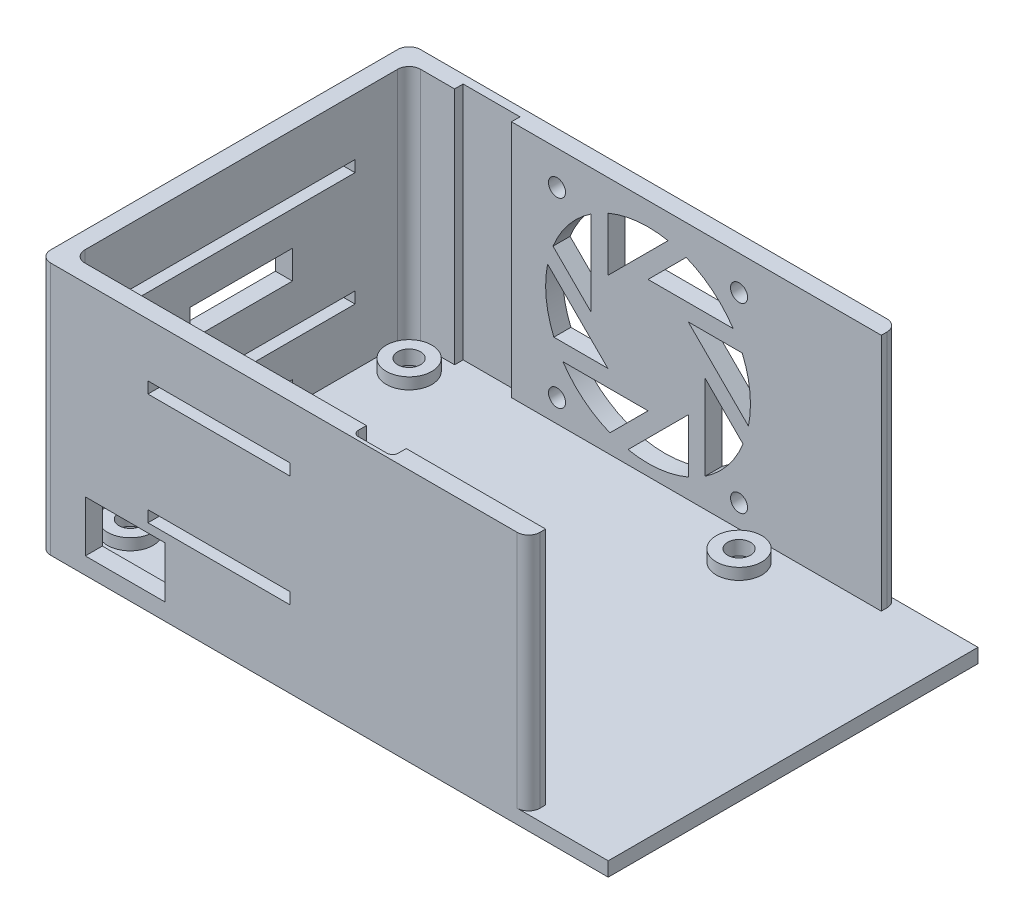
SolidWorks part; units mm, degrees
ref_plane "Front Plane" through (0, 0, 0) normal (0, 0, 1) x (1, 0, 0)
ref_plane "Top Plane" through (0, 0, 0) normal (0, 1, 0) x (1, 0, 0)
ref_plane "Right Plane" through (0, 0, 0) normal (1, 0, 0) x (0, 0, -1)
sketch "Sketch1" plane through (0, 0, 0) normal (0, 1, 0) x (1, 0, 0)
  line L1 (-50, 32.5) -> (50, 32.5)
  line L2 (-50, 32.5) -> (-50, -32.5)
  line L3 (-50, -32.5) -> (50, -32.5)
  line L4 (50, 32.5) -> (50, -32.5)
  line L5 (-50, 32.5) -> (50, -32.5) construction
  line L6 (-50, -32.5) -> (50, 32.5) construction
  point P0 (0, 0)
  dimension "D1" = 100
  dimension "D2" = 65
extrude "Boss-Extrude1" add sketch "Sketch1" along normal blind 2.5
sketch "Sketch2" plane through (0, 2.5, 0) normal (0, 1, 0) x (1, 0, 0)
  line L0 (-13, 32.5) -> (-13, -32.5) construction
  line L1 (50, 32.5) -> (-50, 32.5) construction
  line L2 (-50, -32.5) -> (50, -32.5) construction
  line L3 (-50, 0) -> (50, 0) construction
  line L4 (-50, 32.5) -> (-50, -32.5) construction
  line L5 (50, -32.5) -> (50, 32.5) construction
  line L6 (-42, -24.5) -> (-42, 24.5) construction
  line L7 (16, -24.5) -> (16, 24.5) construction
  circle A0 centre (-42, 24.5) radius 2
  circle A1 centre (-42, -24.5) radius 2
  circle A2 centre (16, -24.5) radius 2
  circle A3 centre (16, 24.5) radius 2
  point P17 (-42, 0)
  point P22 (16, 0)
  dimension "D1" = 4
  dimension "D2" = 24.5
  dimension "D3" = 29
  dimension "D4" = 13
extrude "Cut-Extrude1" cut sketch "Sketch2" against normal through all
sketch "Sketch3" plane through (0, 2.5, 0) normal (0, 1, 0) x (1, 0, 0)
  circle A0 centre (-42, 24.5) radius 4
  circle A1 centre (-42, 24.5) radius 2
  circle A2 centre (16, 24.5) radius 2
  circle A3 centre (16, 24.5) radius 4
  circle A4 centre (16, -24.5) radius 4
  circle A5 centre (16, -24.5) radius 2
  circle A6 centre (-42, -24.5) radius 2
  circle A7 centre (-42, -24.5) radius 4
  circle A8 centre (-42, 24.5) radius 2 construction
  circle A9 centre (-42, -24.5) radius 2 construction
  circle A10 centre (16, 24.5) radius 2 construction
  circle A11 centre (16, -24.5) radius 2 construction
  dimension "D3" = 2
extrude "Boss-Extrude2" add sketch "Sketch3" along normal blind 2
sketch "Sketch4" plane through (0, 0, 0) normal (0, -1, 0) x (-1, 0, 0)
  line L0 (50, 0) -> (-50, 0) construction
  line L1 (42, -28.1084) -> (45.125, -26.3042)
  line L2 (45.125, -26.3042) -> (45.125, -22.6958)
  line L3 (45.125, -22.6958) -> (42, -20.8916)
  line L4 (42, -20.8916) -> (38.875, -22.6958)
  line L5 (38.875, -22.6958) -> (38.875, -26.3042)
  line L6 (38.875, -26.3042) -> (42, -28.1084)
  line L7 (50, 32.5) -> (50, -32.5) construction
  line L8 (-50, -32.5) -> (-50, 32.5) construction
  line L9 (-16, -24.5) -> (42, -24.5) construction
  line L10 (13, -24.5) -> (13, 24.5) construction
  line L11 (-12.875, -26.3042) -> (-16, -28.1084)
  line L12 (-12.875, -22.6958) -> (-12.875, -26.3042)
  line L13 (-16, -20.8916) -> (-12.875, -22.6958)
  line L14 (-19.125, -22.6958) -> (-16, -20.8916)
  line L15 (-16, -28.1084) -> (-19.125, -26.3042)
  line L16 (-19.125, -26.3042) -> (-19.125, -22.6958)
  line L17 (-16, 24.5) -> (42, 24.5) construction
  line L18 (-19.125, 26.3042) -> (-19.125, 22.6958)
  line L19 (-16, 28.1084) -> (-19.125, 26.3042)
  line L20 (-19.125, 22.6958) -> (-16, 20.8916)
  line L21 (-16, 20.8916) -> (-12.875, 22.6958)
  line L22 (-12.875, 22.6958) -> (-12.875, 26.3042)
  line L23 (-12.875, 26.3042) -> (-16, 28.1084)
  line L24 (38.875, 26.3042) -> (42, 28.1084)
  line L25 (38.875, 22.6958) -> (38.875, 26.3042)
  line L26 (42, 20.8916) -> (38.875, 22.6958)
  line L27 (45.125, 22.6958) -> (42, 20.8916)
  line L28 (45.125, 26.3042) -> (45.125, 22.6958)
  line L29 (42, 28.1084) -> (45.125, 26.3042)
  circle A0 centre (42, -24.5) radius 3.125 construction
  circle A1 centre (-16, -24.5) radius 3.125 construction
  circle A2 centre (-16, 24.5) radius 3.125 construction
  circle A3 centre (42, 24.5) radius 3.125 construction
  point P31 (13, 0)
  dimension "D1" = 6.25
extrude "Cut-Extrude2" cut sketch "Sketch4" against normal blind 2
sketch "Sketch5" plane through (0, 2.5, 0) normal (0, 1, 0) x (1, 0, 0)
  line L0 (-50, 0) -> (50, 0) construction
  line L1 (-50, 32.5) -> (-50, -32.5) construction
  line L2 (50, -32.5) -> (50, 32.5) construction
  line L4 (-25, -9) -> (-50, -9)
  line L5 (-25, -9) -> (-25, 9)
  line L6 (-25, 9) -> (-50, 9)
  line L7 (-50, -9) -> (-50, 9)
  line L8 (-25, -9) -> (-50, 9) construction
  line L9 (-25, 9) -> (-50, -9) construction
  point P6 (-37.5, 0)
  dimension "D1" = 25
  dimension "D2" = 18
extrude "Cut-Extrude3" cut sketch "Sketch5" against normal blind 1
sketch "Sketch6" plane through (0, 2.5, 0) normal (0, 1, 0) x (1, 0, 0)
  line L0 (-50, 0) -> (0, 0) construction
  line L1 (-50, 32.5) -> (36, 32.5)
  line L2 (-50, 32.5) -> (-50, 29.5)
  line L3 (-50, 29.5) -> (36, 29.5)
  line L4 (36, 32.5) -> (36, 29.5)
  line L5 (-50, 9) -> (-50, -9) construction
  line L7 (36, -32.5) -> (36, -29.5)
  line L8 (-50, -29.5) -> (36, -29.5)
  line L9 (-50, -32.5) -> (-50, -29.5)
  line L10 (-50, -32.5) -> (36, -32.5)
  circle A0 centre (16, 24.5) radius 2 construction
  dimension "D1" = 3
  dimension "D2" = 20
extrude "Boss-Extrude3" add sketch "Sketch6" along normal blind 42
sketch "Sketch7" plane through (0, 44.5, 0) normal (0, 1, 0) x (1, 0, 0)
  line L0 (7.9988, -30.5371) -> (7.9988, -29.5) construction
  line L1 (6.0238, -30.5371) -> (9.9738, -30.5371) construction
  line L2 (36, -29.5) -> (-50, -29.5) construction
  line L3 (10.4988, -30.3621) -> (10.4988, -28.0371) construction
  line L4 (4.4988, -27.1) -> (11.4988, -27.1)
  line L5 (4.4988, -27.1) -> (4.4988, -30.9)
  line L6 (5.4988, -31.9) -> (10.4988, -31.9)
  line L7 (11.4988, -27.1) -> (11.4988, -30.9)
  line L8 (4.4988, -27.1) -> (11.4988, -31.9) construction
  line L9 (4.4988, -31.9) -> (11.4988, -27.1) construction
  line L10 (-50, -32.5) -> (36, -32.5) construction
  arc A0 (10.4988, -31.9) -> (11.4988, -30.9) centre (10.4988, -30.9) ccw
  arc A1 (4.4988, -30.9) -> (5.4988, -31.9) centre (5.4988, -30.9) ccw
  dimension "D3" = 1
  dimension "D1" = 1
  dimension "D2" = 0.6
extrude "Cut-Extrude4" cut sketch "Sketch7" against normal up to surface (42 mm away) up to face at (16, 2.5, 28.5)
sketch "Sketch8" plane through (0, 2.5, 0) normal (0, 1, 0) x (1, 0, 0)
  line L0 (-50, 29.5) -> (36, 29.5) construction
  line L1 (-50, 9) -> (-47, 9)
  line L2 (-50, 9) -> (-50, 29.5)
  line L3 (-50, 29.5) -> (-47, 29.5)
  line L4 (-47, 9) -> (-47, 29.5)
  line L5 (4.4988, -29.5) -> (-50, -29.5) construction
  line L6 (-50, -9) -> (-47, -9)
  line L7 (-50, -9) -> (-50, -29.5)
  line L8 (-50, -29.5) -> (-47, -29.5)
  line L9 (-47, -9) -> (-47, -29.5)
  line L10 (-50, 32.5) -> (-50, 29.5) construction
extrude "Boss-Extrude4" add sketch "Sketch8" along normal up to surface (42 mm away) up to face at (-7, 44.5, -31)
sketch "Sketch9" plane through (-50, 0, 0) normal (-1, 0, 0) x (0, 0, 1)
  line L0 (-9, 14) -> (9, 14) construction
  line L1 (-9, 1.5) -> (-9, 44.5) construction
  line L2 (9, 1.5) -> (9, 44.5) construction
  line L4 (-9, 6.5) -> (9, 6.5)
  line L5 (-9, 6.5) -> (-9, 21.5)
  line L6 (-9, 21.5) -> (9, 21.5)
  line L7 (9, 6.5) -> (9, 21.5)
  line L8 (-9, 6.5) -> (9, 21.5) construction
  line L9 (-9, 21.5) -> (9, 6.5) construction
  line L10 (-9, 1.5) -> (9, 1.5) construction
  line L11 (-9, 44.5) -> (9, 44.5)
  line L12 (-9, 44.5) -> (-9, 26.5)
  line L13 (-9, 26.5) -> (9, 26.5)
  line L14 (9, 44.5) -> (9, 26.5)
  point P6 (0, 14)
  dimension "D1" = 5
  dimension "D2" = 5
  dimension "D3" = 20
extrude "Boss-Extrude5" add sketch "Sketch9" against normal up to surface (3 mm away) up to face at (-47, 23.5, -19.25)
sketch "Sketch12" plane through (0, 0, 32.5) normal (0, 0, 1) x (1, 0, 0)
  line L0 (-18.4059, 44.5) -> (-18.4059, 0) construction
  line L1 (-50, 44.5) -> (36, 44.5) construction
  line L2 (-50, 0) -> (50, 0) construction
  line L3 (41.5941, 6.1) -> (41.5941, 19.6) construction
  line L4 (-30.9059, 13.5) -> (-5.9059, 13.5)
  line L5 (-30.9059, 13.5) -> (-30.9059, 15.5)
  line L6 (-30.9059, 15.5) -> (-5.9059, 15.5)
  line L7 (-5.9059, 13.5) -> (-5.9059, 15.5)
  line L8 (-30.9059, 13.5) -> (-5.9059, 15.5) construction
  line L9 (-30.9059, 15.5) -> (-5.9059, 13.5) construction
  line L10 (-30.9059, 35.1) -> (-5.9059, 35.1)
  line L11 (-30.9059, 35.1) -> (-30.9059, 33.1)
  line L12 (-30.9059, 33.1) -> (-5.9059, 33.1)
  line L13 (-5.9059, 35.1) -> (-5.9059, 33.1)
  line L14 (-30.9059, 35.1) -> (-5.9059, 33.1) construction
  line L15 (-30.9059, 33.1) -> (-5.9059, 35.1) construction
  line L17 (-42.5, 4.5) -> (36.5, 4.5) construction
  line L19 (-42.5, 24.1) -> (36.5, 24.1) construction
  point P6 (-18.4059, 14.5)
  point P11 (-18.4059, 34.1)
  dimension "D1" = 2
  dimension "D2" = 60
  dimension "D3" = 10
  dimension "D4" = 10
  dimension "D5" = 25
extrude "Cut-Extrude5" cut sketch "Sketch12" against normal up to next
sketch "Sketch14" plane through (0, 0, 32.5) normal (0, 0, 1) x (1, 0, 0)
  line L0 (-35.0287, 7.45) -> (-34.7987, 7.45) construction
  line L1 (-41.9137, 2.95) -> (-27.9137, 2.95)
  line L2 (-41.9137, 2.95) -> (-41.9137, 11.95)
  line L3 (-41.9137, 11.95) -> (-27.9137, 11.95)
  line L4 (-27.9137, 2.95) -> (-27.9137, 11.95)
  line L5 (-41.9137, 2.95) -> (-27.9137, 11.95) construction
  line L6 (-41.9137, 11.95) -> (-27.9137, 2.95) construction
  point P0 (-34.9137, 7.45)
  dimension "D1" = 14
  dimension "D2" = 9
extrude "Cut-Extrude7" cut sketch "Sketch14" against normal up to next
fillet "Fillet1" radius 2 6 edges at (36, 23.5, 32.5) (36, 23.5, -32.5) (-50, 22.25, -32.5) (-47, 23.5, -29.5) (-47, 23.5, 29.5) (-50, 22.25, 32.5)
sketch "Sketch15" plane through (0, 44.5, 0) normal (0, 1, 0) x (1, 0, 0)
  line L0 (-45, 29.5) -> (36, 29.5) construction
  line L1 (-39, 29.5) -> (-29, 29.5)
  line L2 (-39, 29.5) -> (-39, 31)
  line L3 (-39, 31) -> (-29, 31)
  line L4 (-29, 29.5) -> (-29, 31)
  circle A0 centre (-42, 24.5) radius 2 construction
  dimension "D1" = 1.5
  dimension "D2" = 10
  dimension "D3" = 3
extrude "Cut-Extrude8" cut sketch "Sketch15" against normal up to surface (42 mm away) up to face at (16, 2.5, 28.5)
sketch "Sketch16" plane through (-50, 0, 0) normal (-1, 0, 0) x (0, 0, 1)
  line L0 (0, 44.5) -> (0, 0) construction
  line L1 (-30.5, 44.5) -> (30.5, 44.5) construction
  line L2 (-30.5, 0) -> (30.5, 0) construction
  line L3 (-9, 21.5) -> (9, 21.5) construction
  line L4 (-20, 14.5) -> (20, 14.5)
  line L5 (-20, 14.5) -> (-20, 12.5)
  line L6 (-20, 12.5) -> (20, 12.5)
  line L7 (20, 14.5) -> (20, 12.5)
  line L8 (-20, 14.5) -> (20, 12.5) construction
  line L9 (-20, 12.5) -> (20, 14.5) construction
  line L11 (-9, 6.5) -> (9, 6.5) construction
  line L12 (-9, 26.5) -> (9, 26.5) construction
  line L13 (-20, 34.5) -> (20, 34.5)
  line L14 (-20, 34.5) -> (-20, 32.5)
  line L15 (-20, 32.5) -> (20, 32.5)
  line L16 (20, 34.5) -> (20, 32.5)
  line L17 (-20, 34.5) -> (20, 32.5) construction
  line L18 (-20, 32.5) -> (20, 34.5) construction
  point P6 (0, 13.5)
  point P11 (0, 21.5)
  point P16 (0, 33.5)
  dimension "D1" = 2
  dimension "D2" = 40
  dimension "D3" = 0
  dimension "D4" = 7
  dimension "D5" = 7
extrude "Cut-Extrude9" cut sketch "Sketch16" against normal up to surface (3 mm away) up to face at (-47, 24, 0)
sketch "Sketch17" plane through (0, 0, -32.5) normal (0, 0, -1) x (-1, 0, 0)
  line L0 (5, 18.8703) -> (5, 26.1297) construction
  line L1 (5, 22.5) -> (-6.5266, 22.5) construction
  circle A0 centre (-11, 38.5) radius 1.5
  circle A1 centre (21, 38.5) radius 1.5
  circle A2 centre (21, 6.5) radius 1.5
  circle A3 centre (-11, 6.5) radius 1.5
  dimension "D1" = 3
  dimension "D2" = 16
  dimension "D3" = 16
  dimension "D4" = 5
  dimension "D5" = 22.5
extrude "Cut-Extrude10" cut sketch "Sketch17" against normal up to next
sketch "Sketch18" plane through (0, 0, -32.5) normal (0, 0, -1) x (-1, 0, 0)
  line L0 (-11, 38.5) -> (21, 6.5) construction
  line L1 (21, 6.5) -> (-11, 6.5) construction
  line L2 (-11, 6.5) -> (-11, 38.5) construction
  line L3 (-11, 38.5) -> (21, 38.5) construction
  line L4 (21, 38.5) -> (21, 6.5) construction
  line L5 (21, 38.5) -> (-11, 6.5) construction
  line L6 (5, 38.5) -> (5, 6.5) construction
  line L7 (-11, 22.5) -> (21, 22.5) construction
  line L8 (12.0711, 29.5711) -> (1.4881, 40.1541)
  line L9 (12.0711, 29.5711) -> (12.0711, 39.0529)
  line L10 (15, 22.5) -> (15, 37.4666)
  line L11 (15, 22.5) -> (21.7047, 29.2047)
  line L12 (12.0711, 15.4289) -> (22.6541, 26.0119)
  line L13 (12.0711, 15.4289) -> (21.5529, 15.4289)
  line L14 (5, 12.5) -> (19.9666, 12.5)
  line L15 (5, 12.5) -> (11.7047, 5.7953)
  line L16 (-2.0711, 15.4289) -> (8.5119, 4.8459)
  line L17 (-2.0711, 15.4289) -> (-2.0711, 5.9471)
  line L18 (-5, 22.5) -> (-5, 7.5334)
  line L19 (5, 32.5) -> (-9.9666, 32.5)
  line L20 (5, 32.5) -> (-1.7047, 39.2047)
  line L21 (-5, 22.5) -> (-11.7047, 15.7953)
  line L22 (-2.0711, 29.5711) -> (-12.6541, 18.9881)
  line L23 (-2.0711, 29.5711) -> (-11.5529, 29.5711)
  line L24 (5, 22.5) -> (5, 32.5) construction
  arc A0 (-1.7047, 39.2047) -> (-9.9666, 32.5) centre (5, 22.5) ccw
  arc A1 (12.0711, 39.0529) -> (1.4881, 40.1541) centre (5, 22.5) ccw
  arc A2 (21.7047, 29.2047) -> (15, 37.4666) centre (5, 22.5) ccw
  arc A3 (21.5529, 15.4289) -> (22.6541, 26.0119) centre (5, 22.5) ccw
  arc A4 (11.7047, 5.7953) -> (19.9666, 12.5) centre (5, 22.5) ccw
  arc A5 (-2.0711, 5.9471) -> (8.5119, 4.8459) centre (5, 22.5) ccw
  arc A6 (-11.7047, 15.7953) -> (-5, 7.5334) centre (5, 22.5) ccw
  arc A7 (-11.5529, 29.5711) -> (-12.6541, 18.9881) centre (5, 22.5) ccw
  dimension "D1" = 36
  dimension "D2" = 10
  dimension "D3" = 8
extrude "Cut-Extrude11" cut sketch "Sketch18" against normal up to next
